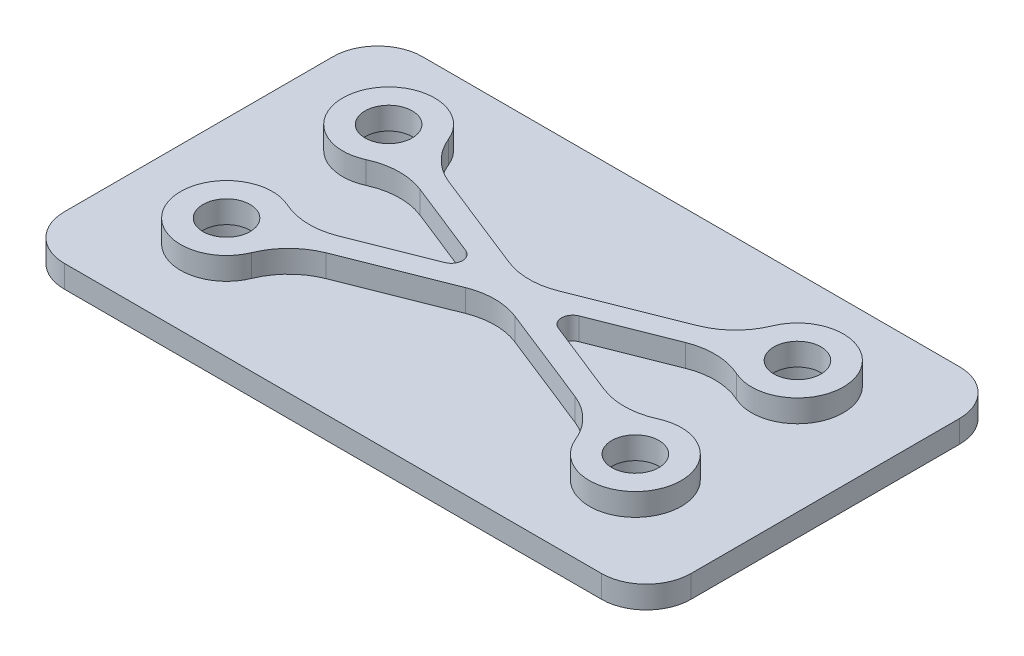
SolidWorks part; units mm, degrees
ref_plane "Front Plane" through (0, 0, 0) normal (0, 0, 1) x (1, 0, 0)
ref_plane "Top Plane" through (0, 0, 0) normal (0, 1, 0) x (1, 0, 0)
ref_plane "Right Plane" through (0, 0, 0) normal (1, 0, 0) x (0, 0, -1)
sketch "Sketch1" plane through (0, 0, 0) normal (0, 1, 0) x (1, 0, 0)
  line L1 (-29, -11.5) -> (29, -11.5) construction
  line L2 (-29, -11.5) -> (-29, 11.5) construction
  line L3 (-29, 11.5) -> (29, 11.5) construction
  line L4 (29, -11.5) -> (29, 11.5) construction
  line L5 (-29, -11.5) -> (29, 11.5) construction
  line L6 (-29, 11.5) -> (29, -11.5) construction
  line L7 (-44.45, -25.4) -> (44.45, -25.4)
  line L8 (-44.45, -25.4) -> (-44.45, 25.4)
  line L9 (-44.45, 25.4) -> (44.45, 25.4)
  line L10 (44.45, -25.4) -> (44.45, 25.4)
  line L11 (-44.45, -25.4) -> (44.45, 25.4) construction
  line L12 (-44.45, 25.4) -> (44.45, -25.4) construction
  point P0 (0, 0)
  point P6 (0, 0)
  point P11 (0, 0)
  dimension "D1" = 58
  dimension "D2" = 23
  dimension "D3" = 88.9
  dimension "D4" = 50.8
extrude "Boss-Extrude1" add sketch "Sketch1" along normal blind 3.175 contours L8 L9 L10 L7
sketch "Sketch2" plane through (0, 3.175, 0) normal (0, 1, 0) x (1, 0, 0)
  line L2 (-29.5852, 10.0243) -> (28.4148, -12.9757)
  line L3 (-26.8507, 8.9399) -> (25.6803, -11.8913)
  line L4 (-28.4148, 12.9757) -> (29.5852, -10.0243)
  line L5 (-25.6803, 11.8913) -> (26.8507, -8.9399)
  line L11 (-28.4148, -12.9757) -> (29.5852, 10.0243)
  line L12 (-25.6803, -11.8913) -> (26.8507, 8.9399)
  line L13 (-29.5852, -10.0243) -> (28.4148, 12.9757)
  line L14 (-26.8507, -8.9399) -> (25.6803, 11.8913)
  circle A0 centre (29, 11.5) radius 3.3427
  circle A1 centre (29, -11.5) radius 3.3427
  circle A2 centre (-29, 11.5) radius 3.3427
  circle A3 centre (-29, -11.5) radius 3.3427
  circle A4 centre (-29, -11.5) radius 6.5177
  circle A5 centre (29, -11.5) radius 6.5177
  circle A6 centre (29, 11.5) radius 6.5177
  circle A7 centre (-29, 11.5) radius 6.5177
  dimension "D5" = 3.175
  dimension "D6" = 6.6854
  dimension "D1" = 1.5875
  dimension "D2" = 1.5875
  dimension "D3" = 1.5875
  dimension "D4" = 1.5875
extrude "Boss-Extrude3" add sketch "Sketch2" along normal blind 3.175 separate body contours L12 A6 L14 A0 | L3 A5 L5 A1 | L14 A4 L12 A3 | L5 A7 L3 A2 | L3 A7 L5 A2 | L12 A4 L14 A3 | A7 L3 L14 L5 | A4 L12 L3 L14 | A6 L14 L5 L12 | A5 L5 L12 L3 | L5 A5 L3 A1 | L14 A6 L12 A0 | L14 L3 L12 L5
fillet "Fillet1" radius 9.525 10 edges at (23.7089, 4.7625, 7.6941) (-23.7089, 4.7625, -7.6941) (-22.5385, 4.7625, 10.6455) (-23.7089, 4.7625, 7.6941) (-22.5385, 4.7625, -10.6455) (22.5385, 4.7625, -10.6455) (0, 4.7625, -1.7078) (23.7089, 4.7625, -7.6941) (0, 4.7625, 1.7078) (22.5385, 4.7625, 10.6455)
fillet "Fillet2" radius 1.5875 2 edges at (-4.3065, 4.7625, 0) (4.3065, 4.7625, 0)
fillet "Fillet3" radius 6.35 4 edges at (44.45, 1.5875, 25.4) (-44.45, 1.5875, 25.4) (-44.45, 1.5875, -25.4) (44.45, 1.5875, -25.4)
sketch "Sketch3" plane through (0, 3.175, 0) normal (0, 1, 0) x (1, 0, 0)
  circle A0 centre (-29, 11.5) radius 3.3427 construction
  circle A1 centre (-29, -11.5) radius 3.3427 construction
  circle A2 centre (29, -11.5) radius 3.3427 construction
  circle A3 centre (29, 11.5) radius 3.3427 construction
  circle A4 centre (-29, 11.5) radius 3.3427
  circle A5 centre (-29, -11.5) radius 3.3427
  circle A6 centre (29, -11.5) radius 3.3427
  circle A7 centre (29, 11.5) radius 3.3427
extrude "Cut-Extrude1" cut sketch "Sketch3" against normal through all both and the other way through all
sketch "Sketch4" plane through (0, 0, 0) normal (0, -1, 0) x (1, 0, 0)
  circle A0 centre (29, 11.5) radius 4.7625
  circle A1 centre (29, -11.5) radius 4.7625
  circle A2 centre (-29, 11.5) radius 4.7625
  circle A3 centre (-29, -11.5) radius 4.7625
  dimension "D1" = 9.525
extrude "Cut-Extrude2" cut sketch "Sketch4" against normal through all
